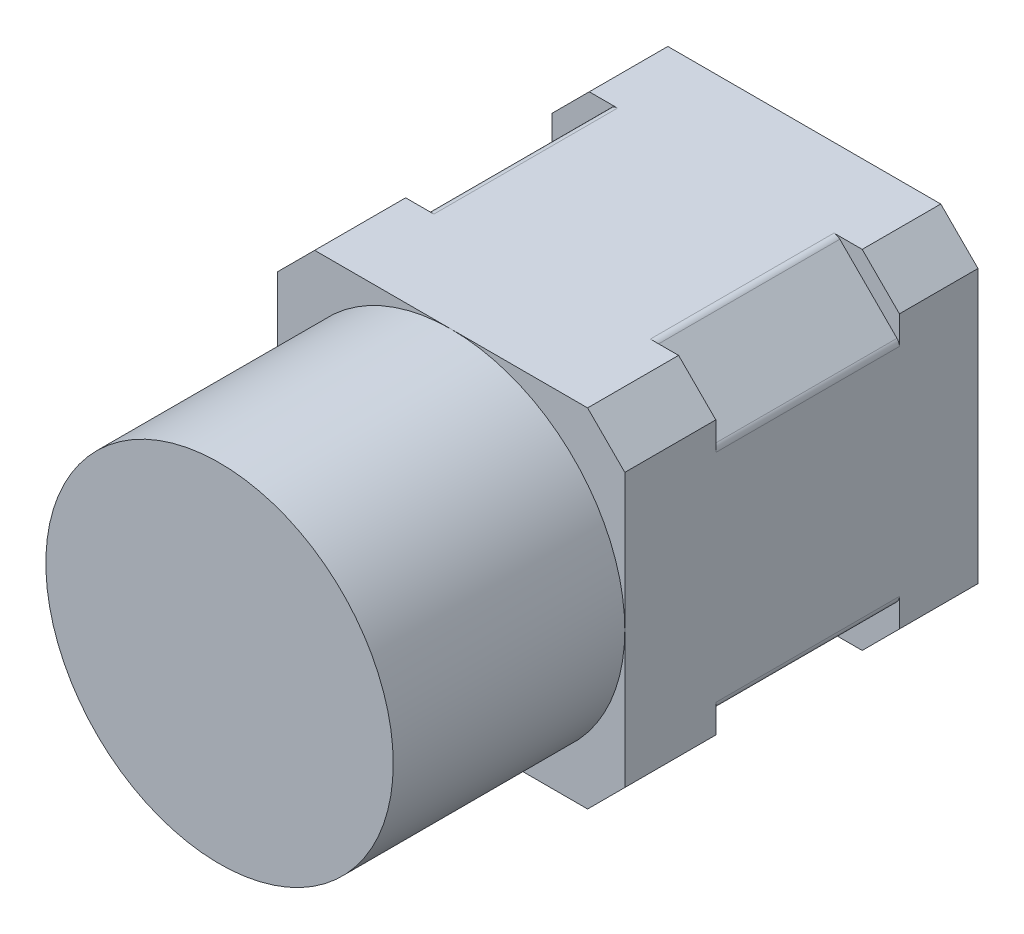
SolidWorks part; units mm, degrees
ref_plane "Front Plane" through (0, 0, 0) normal (0, 0, 1) x (1, 0, 0)
ref_plane "Top Plane" through (0, 0, 0) normal (0, 1, 0) x (1, 0, 0)
ref_plane "Right Plane" through (0, 0, 0) normal (1, 0, 0) x (0, 0, -1)
sketch "Sketch1" plane through (0, 0, 0) normal (0, 0, 1) x (1, 0, 0)
  line L1 (21, 21) -> (-21, 21)
  line L2 (21, 21) -> (21, -21)
  line L3 (21, -21) -> (-21, -21)
  line L4 (-21, 21) -> (-21, -21)
  dimension "D1" = 42
  dimension "D2" = 42
  dimension "D3" = 21
  dimension "D4" = 21
extrude "Boss-Extrude1" add sketch "Sketch1" against normal blind 9.5
chamfer "Chamfer1" distance 4.5 angle 45 4 edges at (-21, -21, -4.75) (21, -21, -4.75) (-21, 21, -4.75) (21, 21, -4.75)
sketch "Sketch3" plane through (0, 0, 0) normal (0, 0, 1) x (1, 0, 0)
  line L0 (-16.5, -21) -> (16.5, -21) construction
  line L1 (13.5, 21) -> (-13.5, 21)
  line L2 (21, 13.5) -> (21, -13.5)
  line L3 (13.5, -21) -> (-13.5, -21)
  line L4 (-21, 13.5) -> (-21, -13.5)
  line L5 (16.5, 21) -> (-16.5, 21) construction
  line L6 (-21, 16.5) -> (-21, -16.5) construction
  line L7 (21, -16.5) -> (21, 16.5) construction
  line L8 (-13.5, 21) -> (-21, 13.5)
  line L9 (21, 13.5) -> (13.5, 21)
  line L10 (21, -13.5) -> (13.5, -21)
  line L11 (-13.5, -21) -> (-21, -13.5)
  point P0 (21, 21)
  point P1 (-21, -21)
  point P2 (21, -21)
  point P3 (-21, 21)
extrude "Boss-Extrude2" add sketch "Sketch3" along normal blind 22.2
fillet "Fillet1" radius 1 8 edges at (21, -13.5, 11.1) (13.5, -21, 11.1) (-13.5, -21, 11.1) (-21, -13.5, 11.1) (-21, 13.5, 11.1) (-13.5, 21, 11.1) (21, 13.5, 11.1) (13.5, 21, 11.1)
sketch "Sketch4" plane through (0, 0, 22.2) normal (0, 0, 1) x (1, 0, 0)
  line L0 (-21, 16.5) -> (-16.5, 21)
  line L1 (-16.5, 21) -> (16.5, 21)
  line L2 (21, 16.5) -> (16.5, 21) construction
  line L3 (16.5, 21) -> (21, 16.5)
  line L4 (21, 16.5) -> (21, -16.5)
  line L5 (21, -16.5) -> (16.5, -21)
  line L6 (16.5, -21) -> (-16.5, -21)
  line L7 (-16.5, -21) -> (-21, -16.5)
  line L8 (-21, -16.5) -> (-21, 16.5)
extrude "Boss-Extrude3" add sketch "Sketch4" along normal blind 11
sketch "Sketch5" plane through (0, 0, 33.2) normal (0, 0, 1) x (1, 0, 0)
  circle A0 centre (0, 0) radius 21
  dimension "D1" = 42
extrude "Boss-Extrude4" add sketch "Sketch5" along normal blind 28
